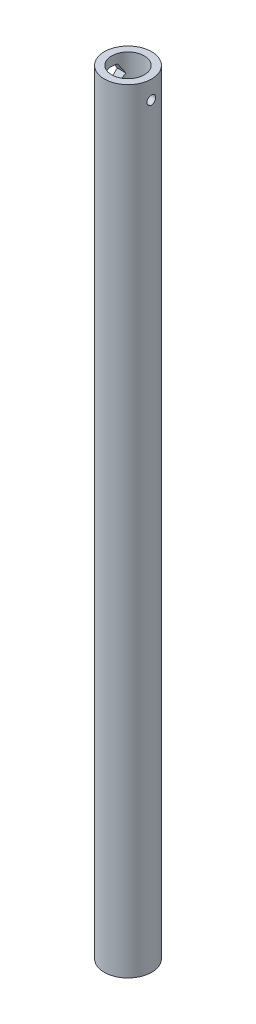
SolidWorks part; units mm, degrees
ref_plane "Front Plane" through (0, 0, 0) normal (0, 0, 1) x (1, 0, 0)
ref_plane "Top Plane" through (0, 0, 0) normal (0, 1, 0) x (1, 0, 0)
ref_plane "Right Plane" through (0, 0, 0) normal (1, 0, 0) x (0, 0, -1)
sketch "Sketch1" plane through (0, 0, 0) normal (0, 1, 0) x (1, 0, 0)
  circle A0 centre (0, 0) radius 5.715
  circle A1 centre (0, 0) radius 8.255
  dimension "D1" = 11.43
  dimension "D2" = 16.51
extrude "Boss-Extrude1" add sketch "Sketch1" along normal blind 269.875
sketch "Sketch2" plane through (0, 0, 0) normal (1, 0, 0) x (0, 0, -1)
  line L0 (-8.255, 269.875) -> (8.255, 269.875) construction
  line L1 (1.8331, 260.35) -> (3.6662, 263.525)
  line L2 (3.6662, 263.525) -> (1.8331, 266.7)
  line L3 (1.8331, 266.7) -> (-1.8331, 266.7)
  line L4 (-1.8331, 266.7) -> (-3.6662, 263.525)
  line L5 (-3.6662, 263.525) -> (-1.8331, 260.35)
  line L6 (-1.8331, 260.35) -> (1.8331, 260.35)
  line L7 (8.255, 269.875) -> (-8.255, 269.875) construction
  line L8 (-8.255, 269.875) -> (-8.255, 0) construction
  circle A0 centre (0, 263.525) radius 3.175 construction
  point P1 (0, 269.875)
  dimension "D1" = 6.35
  dimension "D2" = 6.35
extrude "Cut-Extrude1" cut sketch "Sketch2" against normal through all
sketch "Sketch3" plane through (0, 0, 0) normal (1, 0, 0) x (0, 0, -1)
  line L0 (5.715, 269.875) -> (-5.715, 269.875) construction
  line L1 (-8.255, 269.875) -> (8.255, 269.875) construction
  line L2 (8.255, 269.875) -> (-8.255, 269.875) construction
  line L3 (8.255, 0) -> (8.255, 269.875) construction
  circle A0 centre (0, 263.525) radius 1.524
  point P15 (0, 269.875)
  dimension "D2" = 3.048
  dimension "D1" = 6.35
extrude "Cut-Extrude2" cut sketch "Sketch3" along normal through all
sketch "Sketch4" plane through (0, 0, 0) normal (0, -1, 0) x (1, 0, 0)
  circle A0 centre (0, 0) radius 5.715
  circle A1 centre (0, 0) radius 5.08
  circle A2 centre (0, 0) radius 5.715 construction
  dimension "D1" = 10.16
extrude "Boss-Extrude2" add sketch "Sketch4" against normal blind 3.81
